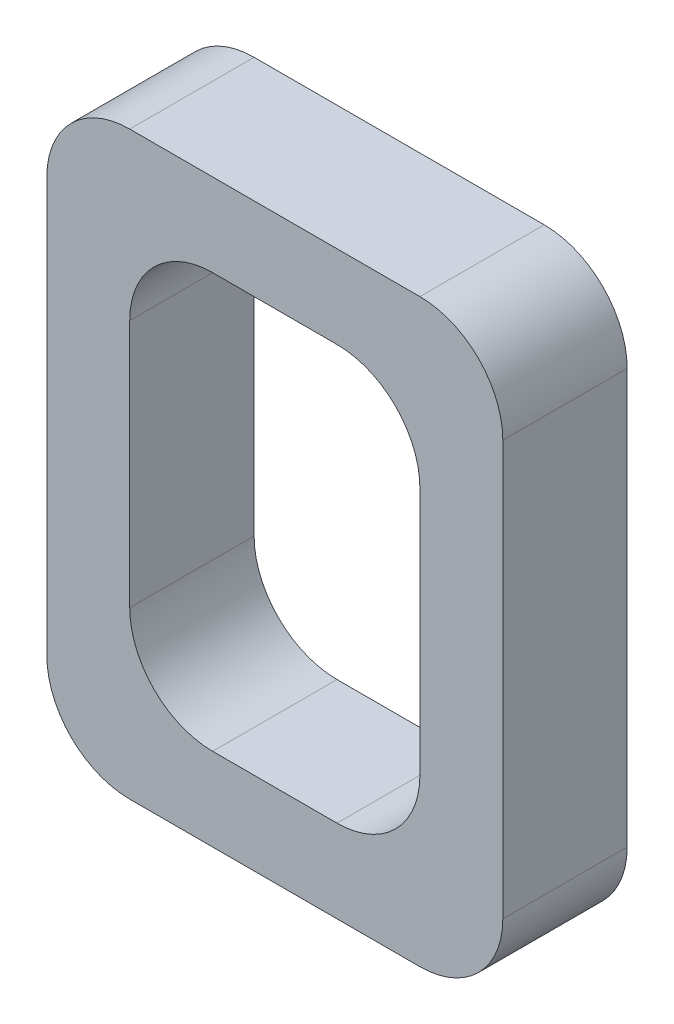
SolidWorks part; units mm, degrees
ref_plane "Plan de face" through (0, 0, 0) normal (0, 0, 1) x (1, 0, 0)
ref_plane "Plan de dessus" through (0, 0, 0) normal (0, 1, 0) x (1, 0, 0)
ref_plane "Plan de droite" through (0, 0, 0) normal (1, 0, 0) x (0, 0, -1)
sketch "Esquisse1" plane through (0, 0, 0) normal (0, 0, 1) x (1, 0, 0)
  line L0 (-17.5, 35) -> (17.5, 35)
  line L1 (-7.5, -25) -> (7.5, -25)
  line L2 (-17.5, -15) -> (-17.5, 15)
  line L3 (-7.5, 25) -> (7.5, 25)
  line L4 (17.5, -15) -> (17.5, 15)
  line L5 (-17.5, -25) -> (17.5, 25) construction
  line L6 (-17.5, 25) -> (17.5, -25) construction
  line L7 (27.5, -25) -> (27.5, 25)
  line L8 (-17.5, -35) -> (17.5, -35)
  line L9 (-27.5, -25) -> (-27.5, 25)
  line L10 (-17.5, 25) -> (17.5, 25) construction
  line L11 (17.5, -25) -> (17.5, 25) construction
  line L12 (-17.5, -25) -> (17.5, -25) construction
  line L13 (-17.5, -25) -> (-17.5, 25) construction
  line L14 (-27.5, 35) -> (27.5, 35) construction
  line L15 (-27.5, -35) -> (-27.5, 35) construction
  line L16 (-27.5, -35) -> (27.5, -35) construction
  line L17 (27.5, -35) -> (27.5, 35) construction
  arc A0 (7.5, 25) -> (17.5, 15) centre (7.5, 15) cw
  arc A1 (17.5, -15) -> (7.5, -25) centre (7.5, -15) cw
  arc A2 (-17.5, -15) -> (-7.5, -25) centre (-7.5, -15) ccw
  arc A3 (-17.5, 15) -> (-7.5, 25) centre (-7.5, 15) cw
  arc A4 (-17.5, 35) -> (-27.5, 25) centre (-17.5, 25) ccw
  arc A5 (-17.5, -35) -> (-27.5, -25) centre (-17.5, -25) cw
  arc A6 (17.5, -35) -> (27.5, -25) centre (17.5, -25) ccw
  arc A7 (27.5, 25) -> (17.5, 35) centre (17.5, 25) ccw
  point P0 (0, 0)
  dimension "D4" = 10
  dimension "D1" = 50
  dimension "D2" = 35
  dimension "D3" = 10
extrude "Boss.-Extru.1" add sketch "Esquisse1" along normal blind 15
